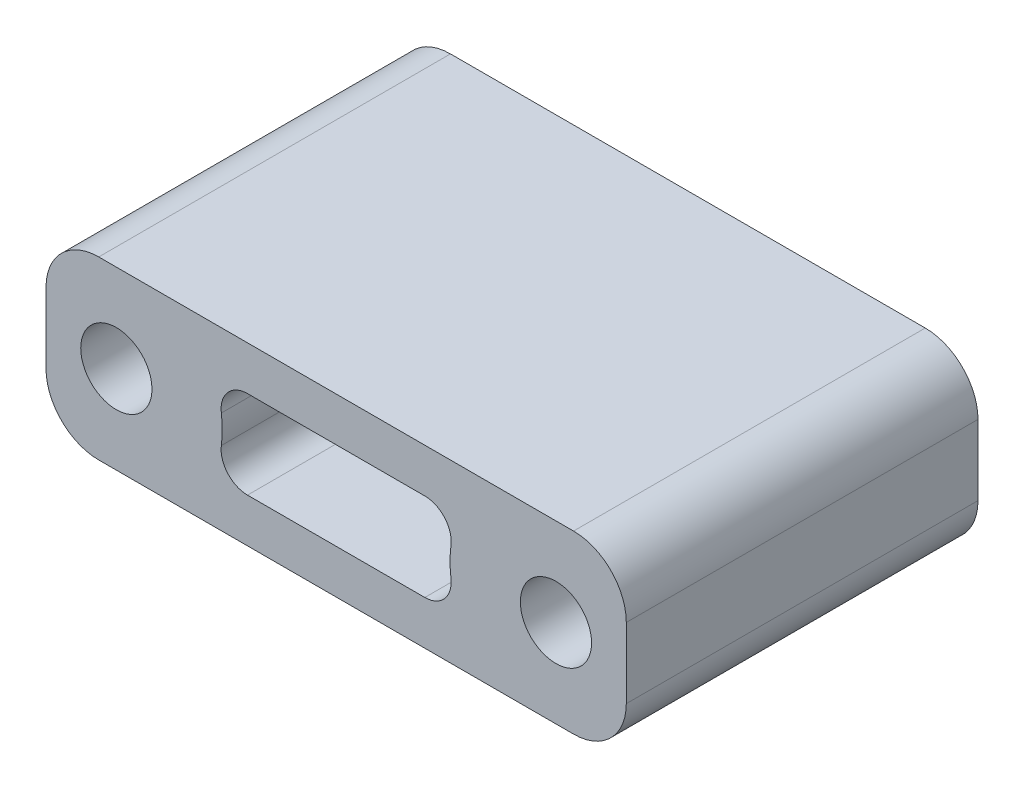
SolidWorks part; units mm, degrees
material "ABS"
ref_plane "前视基准面" through (0, 0, 0) normal (0, 0, 1) x (1, 0, 0)
ref_plane "上视基准面" through (0, 0, 0) normal (0, 1, 0) x (1, 0, 0)
ref_plane "右视基准面" through (0, 0, 0) normal (1, 0, 0) x (0, 0, -1)
other "Configuration Table"
sketch "草图1" plane through (0, 0, 0) normal (0, 0, 1) x (1, 0, 0)
  line L0 (0, 0) -> (12.5, 0) construction
  line L1 (-16.5, -5) -> (16.5, -5)
  line L2 (-16.5, -5) -> (-16.5, 5)
  line L3 (-16.5, 5) -> (16.5, 5)
  line L4 (16.5, -5) -> (16.5, 5)
  line L5 (-16.5, -5) -> (16.5, 5) construction
  line L6 (-16.5, 5) -> (16.5, -5) construction
  line L7 (0, 5) -> (0, 0) construction
  circle A0 centre (12.5, 0) radius 2.025
  circle A1 centre (-12.5, 0) radius 2.025
  point P0 (0, 0)
  dimension "D3" = 4.05
  dimension "D1" = 10
  dimension "D2" = 12.5
  dimension "D4" = 4
extrude "凸台-拉伸1" add sketch "草图1" along normal mid plane 20
sketch "草图2" plane through (0, 0, 10) normal (0, 0, 1) x (1, 0, 0)
  line L0 (-7.0182, 2.5) -> (7.0182, 2.5)
  line L1 (-7.0182, -2.5) -> (7.0182, -2.5)
  line L2 (0, 0) -> (21.9642, 0) construction
  line L3 (16.5, 5) -> (-16.5, 5) construction
  arc A0 (7.0182, 2.5) -> (7.0182, -2.5) centre (12.5, 0) ccw
  arc A1 (-7.0182, -2.5) -> (-7.0182, 2.5) centre (-12.5, 0) ccw
  circle A2 centre (-12.5, 0) radius 2.025 construction
  dimension "D1" = 4
  dimension "D2" = 2.5
extrude "切除-拉伸1" cut sketch "草图2" against normal mid plane 50
fillet "圆角1" radius 1.5 4 edges at (7.0182, 2.5, 0) (7.0182, -2.5, 0) (-7.0182, -2.5, 0) (-7.0182, 2.5, 0)
fillet "圆角2" radius 3 4 edges at (-16.5, -5, 0) (-16.5, 5, 0) (16.5, -5, 0) (16.5, 5, 0)
